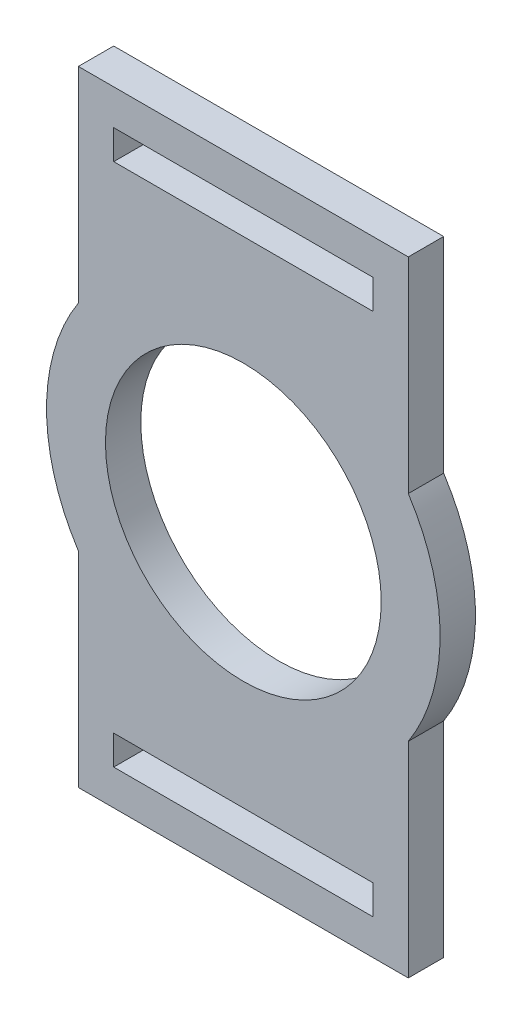
SolidWorks part; units mm, degrees
material "ABS"
ref_plane "Alzado" through (0, 0, 0) normal (0, 0, 1) x (1, 0, 0)
ref_plane "Planta" through (0, 0, 0) normal (0, 1, 0) x (1, 0, 0)
ref_plane "Vista lateral" through (0, 0, 0) normal (1, 0, 0) x (0, 0, -1)
sketch "Croquis1" plane through (0, 0, 0) normal (0, 0, 1) x (1, 0, 0)
  line L0 (11.7, 0) -> (16.7, 0) construction
  line L1 (0, 16.7) -> (0, 21) construction
  line L2 (0, 16.7) -> (0, 11.7) construction
  line L3 (11, 21) -> (-11, 21)
  line L4 (-11, 21) -> (-11, 23.5)
  line L5 (-11, 23.5) -> (11, 23.5)
  line L6 (-14, 9.1044) -> (-14, 26.5)
  line L7 (-14, 26.5) -> (14, 26.5)
  line L8 (14, 9.1044) -> (14, 26.5)
  line L9 (11, 21) -> (11, 23.5)
  line L10 (14, -9.1044) -> (14, -26.5)
  line L11 (-14, -26.5) -> (14, -26.5)
  line L12 (-11, -21) -> (-11, -23.5)
  line L13 (11, -21) -> (-11, -21)
  line L14 (11, -21) -> (11, -23.5)
  line L15 (-11, -23.5) -> (11, -23.5)
  line L16 (-14, -9.1044) -> (-14, -26.5)
  circle A0 centre (0, 0) radius 11.7
  circle A1 centre (0, 0) radius 16.7 construction
  arc A2 (-14, -9.1044) -> (-14, 9.1044) centre (0, 0) cw
  arc A3 (14, 9.1044) -> (14, -9.1044) centre (0, 0) cw
  point P17 (0, 26.5)
  point P18 (0, 23.5)
  dimension "D1" = 23.4
  dimension "D2" = 5
  dimension "D3" = 9.3
  dimension "D4" = 11
  dimension "D5" = 2.5
  dimension "D6" = 3
  dimension "D7" = 3
extrude "Saliente-Extruir1" add sketch "Croquis1" along normal blind 3
